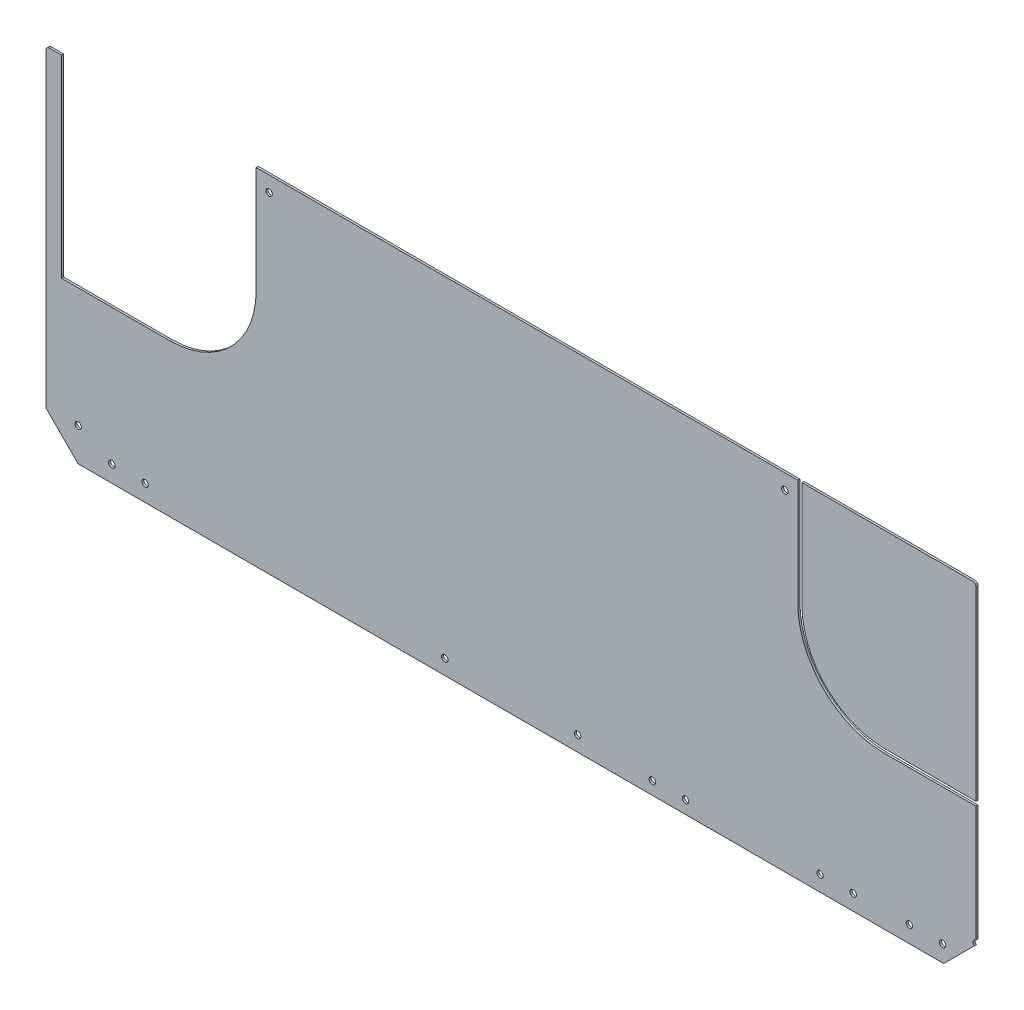
SolidWorks part; units mm, degrees
material "Perspex (TM) GS Acrylic Cast Sheet"
ref_plane "Front Plane" through (0, 0, 0) normal (0, 0, 1) x (1, 0, 0)
ref_plane "Top Plane" through (0, 0, 0) normal (0, 1, 0) x (1, 0, 0)
ref_plane "Right Plane" through (0, 0, 0) normal (1, 0, 0) x (0, 0, -1)
sketch "Sketch1" plane through (0, 0, 0) normal (0, 0, 1) x (1, 0, 0)
  line L1 (-457.2, -304.8) -> (457.2, -304.8)
  line L2 (-457.2, -304.8) -> (-457.2, 304.8)
  line L3 (-457.2, 304.8) -> (457.2, 304.8)
  line L4 (457.2, -304.8) -> (457.2, 304.8)
  line L5 (0, 304.8) -> (0, -304.8) construction
  line L6 (-457.2, 0) -> (457.2, 0) construction
  point P0 (0, 0)
  point P4 (-320.04, 0)
  point P5 (320.04, 0)
  point P6 (0, 213.36)
  point P7 (0, -213.36)
  dimension "Length" = 914.4
  dimension "Width" = 609.6
  dimension "Break" = 137.16
  dimension "D2" = 137.16
  dimension "D1" = 91.44
  dimension "D3" = 91.44
sketch "Sketch2" plane through (0, 0, 0) normal (1, 0, 0) x (0, 0, -1)
  line L0 (-0.7938, -304.8) -> (0.7938, -304.8)
  dimension "Thickness" = 1.5875
sketch "Sketch3" plane through (0, 0, 0) normal (0, 0, 1) x (1, 0, 0)
  line L0 (-457.2, -304.8) -> (-457.2, 304.8) construction
  line L1 (-457.2, -304.8) -> (457.2, -304.8) construction
  line L2 (457.2, -304.8) -> (457.2, 304.8) construction
  line L3 (-457.2, 304.8) -> (457.2, 304.8) construction
  line L4 (-457.2, -304.8) -> (-457.2, 304.8)
  line L5 (-457.2, -304.8) -> (457.2, -304.8)
  line L6 (457.2, -304.8) -> (457.2, 304.8)
  line L7 (-457.2, 304.8) -> (457.2, 304.8)
extrude "Boss-Extrude1" add sketch "Sketch3" along normal mid plane 1.5875
sketch "Sketch4" plane through (0, 0, 0.7937) normal (0, 0, 1) x (1, 0, 0)
  line L17 (-364.7412, -305.5546) -> (-390.1412, -280.1546)
  line L18 (-389.2519, -727.2973) -> (-390.3777, -41.4982) construction
  line L19 (-390.1412, -280.1546) -> (-390.1412, -42.9821)
  line L20 (-387.6012, -40.4421) -> (318.5188, -40.4421)
  line L21 (-364.7412, -305.5546) -> (295.6588, -305.5546)
  line L22 (295.463, -65.7724) -> (296.5888, -751.5715) construction
  line L23 (295.6588, -305.5546) -> (321.0588, -280.1546)
  line L24 (320.863, -65.7307) -> (321.9888, -751.5298) construction
  line L25 (321.0588, -280.1546) -> (321.0588, -42.9821)
  arc A0 (318.5188, -40.4421) -> (321.0588, -42.9821) centre (318.5188, -42.9821) cw
  arc A1 (-390.1412, -42.9821) -> (-387.6012, -40.4421) centre (-387.6012, -42.9821) cw
  point P17 (321.0588, -40.4421)
  point P21 (-390.1412, -40.4421)
  dimension "D1" = 2.54
  dimension "D2" = 2.54
extrude "Cut-Extrude1" cut sketch "Sketch4" against normal blind 2.54 flip side to cut
sketch "Sketch7" plane through (0, 0, 0.7937) normal (0, 0, 1) x (1, 0, 0)
  line L0 (-378.2467, -188.1903) -> (-378.2467, -39.3463)
  line L3 (-378.2467, -39.3463) -> (-229.4027, -39.3463)
  line L10 (-229.4027, -64.7463) -> (-229.4027, -39.3463)
  line L11 (-229.4027, -64.7463) -> (-229.4027, -121.8963)
  line L12 (-352.8467, -188.1903) -> (-295.6967, -188.1903)
  line L13 (-352.8467, -188.1903) -> (-378.2467, -188.1903)
  arc A1 (-229.4027, -121.8963) -> (-295.6967, -188.1903) centre (-295.6967, -121.8963) cw
extrude "Cut-Extrude2" cut sketch "Sketch7" against normal blind 2.54
sketch "Sketch8" plane through (0, 0, 0.7937) normal (0, 0, 1) x (1, 0, 0)
  line L0 (251.1151, -185.0153) -> (333.6651, -185.0153)
  line L1 (333.6651, -39.3463) -> (333.6651, -725.1463) construction
  line L2 (333.6651, -185.0153) -> (333.6651, -39.3463)
  line L3 (187.9961, -121.8963) -> (187.9961, -39.3463)
  line L4 (-378.2467, -39.3463) -> (307.5533, -39.3463) construction
  line L5 (187.9961, -39.3463) -> (333.6651, -39.3463)
  line L6 (251.1151, -188.1903) -> (336.8401, -188.1903)
  line L7 (336.8401, -188.1903) -> (336.8401, -36.1713)
  line L8 (184.8211, -36.1713) -> (336.8401, -36.1713)
  line L9 (184.8211, -121.8963) -> (184.8211, -36.1713)
  arc A0 (187.9961, -121.8963) -> (251.1151, -185.0153) centre (251.1151, -121.8963) ccw
  arc A1 (184.8211, -121.8963) -> (251.1151, -188.1903) centre (251.1151, -121.8963) ccw
  dimension "D1" = 3.175
extrude "Cut-Extrude3" cut sketch "Sketch8" against normal blind 2.54
sketch "Sketch9" plane through (0, 0, 0.7937) normal (0, 0, 1) x (1, 0, 0)
  point P0 (-365.5467, -279.4147)
  point P1 (-339.7911, -292.1147)
  point P3 (-314.3911, -292.1147)
  point P5 (-365.5467, -229.8463)
  point P15 (270.1645, -292.1147)
  point P17 (295.5645, -292.1147)
  point P19 (321.3201, -279.4147)
  point P21 (320.9651, -229.8463)
  point P23 (-219.4967, -52.0463)
  point P25 (174.9151, -52.0463)
hole_wizard "#10 (0.1935) Diameter Hole1" positions "Sketch10" profile "Sketch11" hole size "#10" standard "ANSI Inch" end condition through all
sketch "Sketch10" plane through (0, 0, 0.7937) normal (0, 0, 1) x (1, 0, 0)
  point P0 (-314.3911, -292.1147)
  point P3 (-339.7911, -292.1147)
  point P6 (-365.5467, -279.4147)
  point P21 (295.5645, -292.1147)
  point P24 (270.1645, -292.1147)
  point P27 (321.3201, -279.4147)
  point P31 (174.9151, -52.0463)
  point P34 (-219.4967, -52.0463)
  point P37 (73.5797, -295.0929)
  point P40 (98.9796, -295.0512)
  point P43 (201.8463, -292.9389)
  point P46 (227.2463, -292.8972)
  point P49 (-85.1638, -293.41)
  point P52 (16.4361, -293.2433)
sketch "Sketch11" plane through (-314.3911, -292.1147, 0.7937) normal (1, 0, 0) x (0, -1, 0)
  line L0 (0, 0) -> (0, 1.5875)
  line L1 (0, 1.5875) -> (2.4574, 1.5875)
  line L2 (2.4574, 1.5875) -> (2.4574, 0)
  line L5 (2.4574, 0) -> (0, 0)
  line L11 (0, -6.35) -> (0, 107.95) construction
  dimension "Thru Hole Dia." = 4.9149
  dimension "Thru Hole Depth" = 1.5875
equation "\"D1@Boss-Extrude1\"=\"thickness@sketch2\""
equation "\"Break@Sketch1\" = \"Length@Sketch1\" * 0.15"
equation "\"D2@Sketch1\" = \"Break@Sketch1\""
equation "\"D1@Sketch1\"=\"Width@Sketch1\"*0.15"
equation "\"D3@Sketch1\"=\"D1@Sketch1\""
